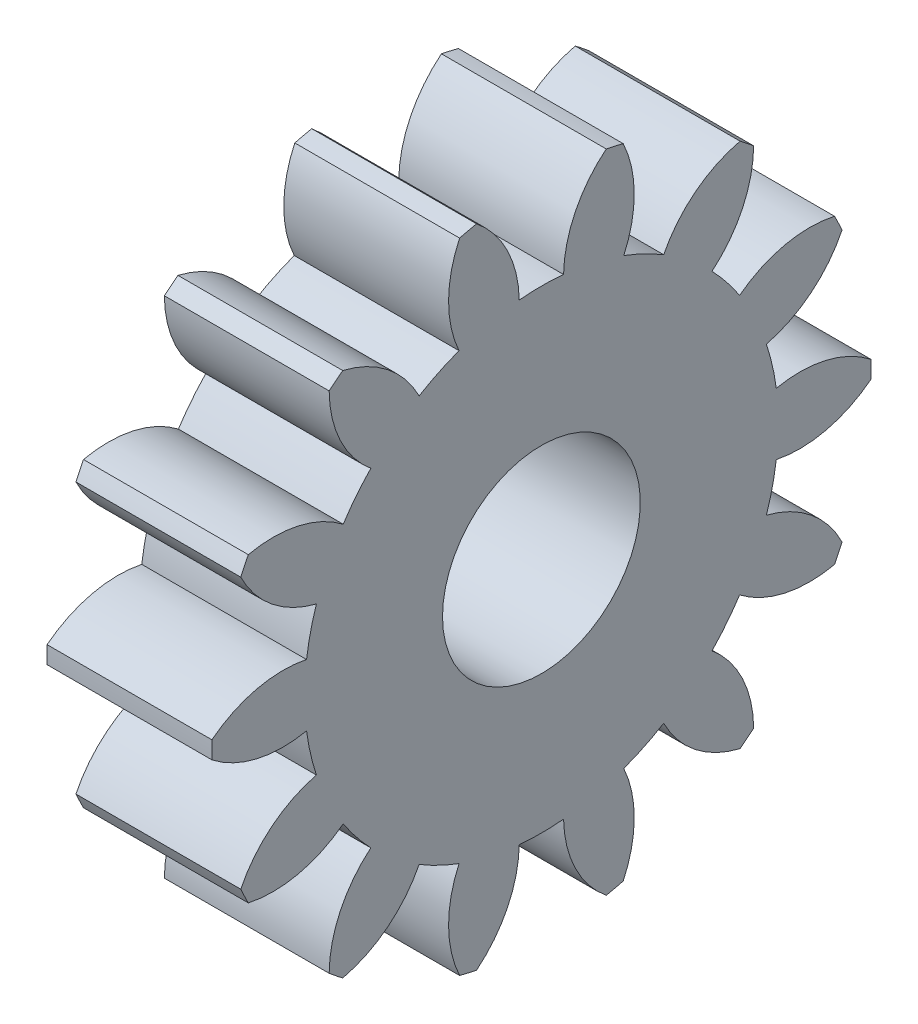
SolidWorks part; units mm, degrees
ref_plane "Plane1" through (0, 0, 0) normal (0, 0, 1) x (1, 0, 0)
ref_plane "Plane2" through (0, 0, 0) normal (0, 1, 0) x (1, 0, 0)
ref_plane "Plane3" through (0, 0, 0) normal (1, 0, 0) x (0, 0, -1)
sketch "HoldingSke" plane through (0, 0, 0) normal (0, 1, 0) x (1, 0, 0)
  line L0 (0, 0) -> (0.7762, -0.1935)
  line L1 (-15, 0) -> (100, 0) construction
  line L2 (0, 0) -> (-2.1039, 2.3779)
  line L3 (0, 0) -> (-11.863, 4.5341)
  line L4 (0, 0) -> (8.3795, 2.0892)
  line L5 (0, 0) -> (-46.8476, -17.4728)
  line L6 (0, 0) -> (-4.1448, -2.7965)
  line L7 (-2.1039, 2.3779) -> (8.6586, 51.2059)
  line L8 (-76.2, 54.61) -> (-75.2, 54.61)
  line L9 (-71.009, 38.7566) -> (-53.1078, 45.2721)
  line L10 (-76.2, 71.12) -> (104.1128, 71.12)
  line L11 (0, 0) -> (-5, 0)
  line L12 (-76.2, 101.6) -> (-76.155, 101.6)
  line L13 (24.9733, 27.94) -> (52.9518, 28.4284)
  line L14 (24.9733, 27.94) -> (24.9743, 27.94)
  line L15 (24.9733, 27.94) -> (100.4006, 29.5858)
  line L16 (-63.627, -1.25) -> (-12.827, -1.25)
  circle A0 centre (0, 0) radius 3
  circle A1 centre (0, 0) radius 7.1865
  circle A2 centre (0, 0) radius 37.5
  circle A3 centre (0, 0) radius 3
  dimension "MHD" = 14.373
  dimension "Hub_dia" = 75
  dimension "Bore" = 6
  dimension "MBD" = 6
  dimension "Num_teeth" = 14
  dimension "Pitch" = 0.8
  dimension "Overall_len" = 50
  dimension "Show_teeth" = 14
  dimension "Thickness" = 5
  dimension "OAL" = 50.0001
  dimension "T_dim" = 1
  dimension "Ap" = 20
  dimension "H" = 19.05
  dimension "Pitch_radius" = 180.3128
  dimension "Width" = 5
  dimension "Backlash" = 0.045
  dimension "Addendum_fac" = 1
  dimension "Dedendum_fac" = 1.25
  dimension "Clearance_fac" = 0.25
  dimension "Dedendum_add" = 0.001
  dimension "Module" = 1.25
sketch "BasProSke" plane through (0, 0, 0) normal (0, 1, 0) x (1, 0, 0)
  line L0 (-10, 0) -> (60, 0) construction
  line L1 (0, 0) -> (0, 10)
  line L2 (0, 0) -> (5, 0)
  line L3 (5, 0) -> (5, 10)
  line L4 (5, 10) -> (0, 10)
  dimension "Thickness" = 5
  dimension "Diameter" = 20
revolve "Base-Revolve" add sketch "BasProSke" angle 360 about L0
sketch "TooCutSke" plane through (0, 0, 0) normal (1, 0, 0) x (0, 0, -1)
  line L1 (0, 0) -> (0, 107) construction
  line L2 (0, 0) -> (-1.0584, 8.6858) construction
  line L3 (0, 0) -> (-3.8734, 16.9706) construction
  line L4 (-1.0584, 8.6858) -> (-1.9367, 8.4853) construction
  arc A0 (0.6719, 7.155) -> (-0.6719, 7.155) centre (0, 0) ccw
  arc A1 (1.993, 9.8253) -> (-1.993, 9.8253) centre (0, 0) ccw
  circle A2 centre (0, 0) radius 8.75 construction
  circle A3 centre (0, 0) radius 8.2223 construction
  arc A4 (-0.6719, 7.155) -> (-1.993, 9.8253) centre (-4.1712, 7.0857) ccw
  arc A5 (1.993, 9.8253) -> (0.6719, 7.155) centre (4.1712, 7.0857) ccw
  dimension "Root_dia" = 14.373
  dimension "Overcut_dia" = 20.0508
  dimension "Pitch_dia" = 17.5
  dimension "Base_dia" = 16.4446
  dimension "Flank_rad" = 3.5
  dimension "Half_ang" = 12.857
  dimension "Half_CT" = 0.9009
extrude "ToothCut" cut sketch "TooCutSke" along normal through all
fillet "Breaks" [suppressed] radius 0.025
fillet "RootFillets" [suppressed] radius 0.3135
pattern_circular "TeethCuts" count 14 every 25.714 about axis through (-10, 0, 0) along (1, 0, 0) of "ToothCut", "RootFillets", "Breaks"
sketch "HubNeaOneSke" plane through (0, 0, 0) normal (-1, 0, 0) x (0, 0, 1)
  circle A0 centre (0, 0) radius 7.1865
  dimension "Diameter" = 14.373
extrude "HubNearOne" [suppressed] add sketch "HubNeaOneSke" along normal blind 45.0001
sketch "HubNeaBotSke" plane through (0, 0, 0) normal (-1, 0, 0) x (0, 0, 1)
  circle A0 centre (0, 0) radius 7.1865
  dimension "Diameter" = 14.373
extrude "HubNearBoth" [suppressed] add sketch "HubNeaBotSke" along normal blind 22.5
ref_plane "FarPln" through (5, 0, 0) normal (1, 0, 0) x (0, 0, -1)
sketch "HubFarSke" plane through (5, 0, 0) normal (1, 0, 0) x (0, 0, -1)
  circle A0 centre (0, 0) radius 7.1865
  dimension "Diameter" = 14.373
extrude "HubFar" [suppressed] add sketch "HubFarSke" along normal blind 22.5
sketch "BorSke" plane through (0, 0, 0) normal (1, 0, 0) x (0, 0, -1)
  circle A0 centre (0, 0) radius 3
  dimension "Diameter" = 6
extrude "Bore" cut sketch "BorSke" along normal mid plane 100.0001
sketch "KeySke" plane through (0, 0, 0) normal (1, 0, 0) x (0, 0, -1)
  line L0 (-1, 0) -> (-1, 4)
  line L1 (-1, 4) -> (1, 4)
  line L2 (1, 4) -> (1, 0)
  line L3 (0, 0) -> (0, 34) construction
  line L4 (-1, 0) -> (1, 0)
  dimension "Offset" = 4
  dimension "Width" = 2
extrude "Keyway" [suppressed] cut sketch "KeySke" along normal mid plane 100.0001
pattern_circular "Keyway2" [suppressed] count 2 every 90 about axis through (-10, 0, 0) along (1, 0, 0)
equation "' \"Module@HoldingSke\" = 6.35"
equation "' \"Num_teeth@HoldingSke\" = 12"
equation "' \"Ap@HoldingSke\" =  20"
equation "' \"Ap@HoldingSke\" = 20"
equation "' \"Width@HoldingSke\" = 0.5 * 25.4"
equation "' \"Hub_dia@HoldingSke\"= 1 * 25.4"
equation "' \"Hub_dia@HoldingSke\" = 1 * 25.4"
equation "' \"Overall_len@HoldingSke\" = 1.0 * 25.4"
equation "' \"Bore@HoldingSke\" = 0.75 * 25.4"
equation "' \"T_dim@HoldingSke\" = 0.1 * 25.4"
equation "' \"Width@KeySke\" = 0.25 * 25.4"
equation "' \"Show_teeth@HoldingSke\" = 13"
equation "' \"Backlash@HoldingSke\" = 0.009 * 25.4"
equation "' \"Addendum_fac@HoldingSke\" = 1.0"
equation "' \"Dedendum_fac@HoldingSke\" = 1.25"
equation "' \"Dedendum_add@HoldingSke\" = 0.00005 * 25.4"
equation "' \"Clearance_fac@HoldingSke\" = 0.25"
equation "\"Pitch@HoldingSke\" = 1 / \"Module@HoldingSke\""
equation "\"Overcut_dia@TooCutSke\" = (\"Num_teeth@HoldingSke\" + 2 * \"Addendum_fac@HoldingSke\") / \"Pitch@HoldingSke\" + 0.002 * 25.4"
equation "\"Pitch_dia@TooCutSke\" = \"Num_teeth@HoldingSke\" / \"Pitch@HoldingSke\""
equation "\"Base_dia@TooCutSke\" = \"Num_teeth@HoldingSke\" / \"Pitch@HoldingSke\" * cos((\"Ap@HoldingSke\"  * 3.14159265 / 180))"
equation "\"Root_dia@TooCutSke\" = (\"Num_teeth@HoldingSke\" + 2) / \"Pitch@HoldingSke\" - 2 * (\"Addendum_fac@HoldingSke\" + \"Dedendum_fac@HoldingSke\") / \"Pitch@HoldingSke\" - \"Dedendum_add@HoldingSke\" * 2"
equation "\"Half_ang@TooCutSke\" = 180 / \"Num_teeth@HoldingSke\""
equation "\"Half_CT@TooCutSke\" = \"Num_teeth@HoldingSke\" / \"Pitch@HoldingSke\" * sin((3.14159265 / 2 / \"Num_teeth@HoldingSke\")) / 2 - 7 * \"Backlash@HoldingSke\" / 4"
equation "\"Flank_rad@TooCutSke\" = \"Num_teeth@HoldingSke\" / \"Pitch@HoldingSke\" / 5"
equation "\"Radius@RootFillets\" = \"Clearance_fac@HoldingSke\" / \"Pitch@HoldingSke\" + \"Dedendum_add@HoldingSke\""
equation "\"Break_rad@Breaks\" = 0.02 / \"Pitch@HoldingSke\""
equation "\"Thickness@HoldingSke\" = \"Width@HoldingSke\""
equation "\"OAL@HoldingSke\" = \"Thickness@HoldingSke\""
equation "\"MHD@HoldingSke\" = (\"Num_teeth@HoldingSke\" + 2) / \"Pitch@HoldingSke\" - 2 * (\"Addendum_fac@HoldingSke\" + \"Dedendum_fac@HoldingSke\")  / \"Pitch@HoldingSke\" - \"Dedendum_add@HoldingSke\" * 2"
equation "\"MBD@HoldingSke\" = (\"Num_teeth@HoldingSke\" + 2) / \"Pitch@HoldingSke\" - 2 * (\"Addendum_fac@HoldingSke\" + \"Dedendum_fac@HoldingSke\")  / \"Pitch@HoldingSke\" - \"Dedendum_add@HoldingSke\" * 2 - 0.002 * 25.4"
equation "\"MHD@HoldingSke\" = ((sgn( \"MHD@HoldingSke\" - \"Hub_dia@HoldingSke\" )-1)*( \"MHD@HoldingSke\" - \"Hub_dia@HoldingSke\" ))/-2+ \"Hub_dia@HoldingSke\""
equation "\"MBD@HoldingSke\" = ((sgn( \"MBD@HoldingSke\" - \"Bore@HoldingSke\" )-1)*( \"MBD@HoldingSke\" - \"Bore@HoldingSke\" ))/-2+ \"Bore@HoldingSke\""
equation "\"OAL@HoldingSke\" = ((sgn( \"OAL@HoldingSke\" - \"Overall_len@HoldingSke\" )+1)*( \"OAL@HoldingSke\" - \"Overall_len@HoldingSke\" ))/2 + \"Overall_len@HoldingSke\" + 0.000002 * 25.4"
equation "\"Num_teeth@TeethCuts\" = int( \"Show_teeth@HoldingSke\" ) + 1"
equation "\"Num_teeth@TeethCuts\" = ((sgn( \"Num_teeth@TeethCuts\" - \"Num_teeth@HoldingSke\" )-1)*( \"Num_teeth@TeethCuts\" - \"Num_teeth@HoldingSke\" ))/-2+ \"Num_teeth@HoldingSke\""
equation "\"Num_teeth@TeethCuts\" = ((sgn( \"Num_teeth@TeethCuts\" - 2.0)+1)*( \"Num_teeth@TeethCuts\" - 2.0))/2 +2.0"
equation "\"Angle@TeethCuts\" = 360.0 / \"Num_teeth@HoldingSke\""
equation "\"Diameter@BasProSke\" = (\"Num_teeth@HoldingSke\" + 2 * \"Addendum_fac@HoldingSke\") / \"Pitch@HoldingSke\""
equation "\"Thickness@BasProSke\"  = \"Thickness@HoldingSke\""
equation "' \"Fillet_rad@BasProSke\" =  \"Thickness@HoldingSke\" * 0.05"
equation "' \"Fillet_rad@BasProSke\" = \"Thickness@HoldingSke\" * 0.05"
equation "\"MHD@HoldingSke\" = ((sgn( \"MHD@HoldingSke\" - \"Root_dia@TooCutSke\" )-1)*( \"MHD@HoldingSke\" - \"Root_dia@TooCutSke\" ))/-2+ \"Root_dia@TooCutSke\""
equation "\"Diameter@HubNeaOneSke\" = \"MHD@HoldingSke\""
equation "\"Length@HubNearOne\" = \"OAL@HoldingSke\" - \"Thickness@BasProSke\""
equation "\"Diameter@HubNeaBotSke\" = \"MHD@HoldingSke\""
equation "\"Length@HubNearBoth\" = ( \"OAL@HoldingSke\" - \"Thickness@BasProSke\" ) / 2.0"
equation "\"Thickness@FarPln\" = \"Thickness@BasProSke\""
equation "\"Diameter@HubFarSke\" = \"MHD@HoldingSke\""
equation "\"Length@HubFar\" = ( \"OAL@HoldingSke\" - \"Thickness@BasProSke\" ) / 2.0"
equation "\"Diameter@BorSke\" = \"MBD@HoldingSke\""
equation "\"D1@Bore\" = \"OAL@HoldingSke\" * 2.0"
equation "\"D1@Keyway\" = \"OAL@HoldingSke\" * 2.0"
equation "\"Offset@KeySke\" = \"T_dim@HoldingSke\" + \"MBD@HoldingSke\" / 2.0"
